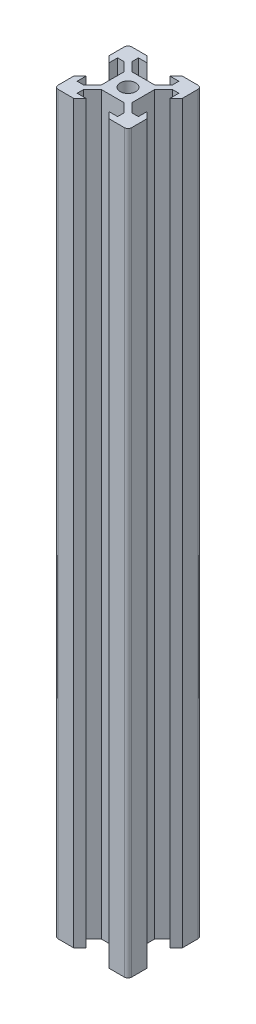
SolidWorks part; units mm, degrees
material "1060 Alloy"
ref_plane "Front Plane" through (0, 0, 0) normal (0, 0, 1) x (1, 0, 0)
ref_plane "Top Plane" through (0, 0, 0) normal (0, 1, 0) x (1, 0, 0)
ref_plane "Right Plane" through (0, 0, 0) normal (1, 0, 0) x (0, 0, -1)
ref_plane "End Plane" through (0, 200, 0) normal (0, 1, 0) x (1, 0, 0)
sketch "MasterLayoutSketch" plane through (0, 0, 0) normal (0, 1, 0) x (1, 0, 0)
  line L0 (-8.325, 3.1) -> (-8.325, 5.5)
  line L1 (-10, -10) -> (10, -10) construction
  line L2 (-10, -10) -> (-10, 10) construction
  line L3 (-10, 10) -> (10, 10) construction
  line L4 (10, -10) -> (10, 10) construction
  line L5 (-10, -10) -> (10, 10) construction
  line L6 (-10, 10) -> (10, -10) construction
  line L7 (-4.775, 10) -> (-3.1, 8.325)
  line L10 (-8.325, 5.5) -> (-6.5607, 5.5)
  line L11 (-10, 4.775) -> (-8.325, 3.1)
  line L12 (-5.5, 8.325) -> (-5.5, 6.5607)
  line L13 (-3.1, 8.325) -> (-5.5, 8.325)
  line L14 (-10, 10) -> (-10, 4.775)
  line L19 (3.1, 8.325) -> (5.5, 8.325)
  line L20 (10, 4.775) -> (8.325, 3.1)
  line L21 (-10, 10) -> (-4.775, 10)
  line L22 (-6.5607, 5.5) -> (-4.1607, 3.1)
  line L23 (-5.5, 6.5607) -> (-3.1, 4.1607)
  line L24 (5.5, 8.325) -> (5.5, 6.5607)
  line L25 (4.775, 10) -> (3.1, 8.325)
  line L26 (8.325, 5.5) -> (6.5607, 5.5)
  line L27 (8.325, 3.1) -> (8.325, 5.5)
  line L28 (10, 10) -> (4.775, 10)
  line L29 (10, 10) -> (10, 4.775)
  line L30 (5.5, 6.5607) -> (3.1, 4.1607)
  line L31 (6.5607, 5.5) -> (4.1607, 3.1)
  line L32 (8.325, -3.1) -> (8.325, -5.5)
  line L33 (4.775, -10) -> (3.1, -8.325)
  line L34 (8.325, -5.5) -> (6.5607, -5.5)
  line L35 (10, -4.775) -> (8.325, -3.1)
  line L36 (5.5, -8.325) -> (5.5, -6.5607)
  line L37 (3.1, -8.325) -> (5.5, -8.325)
  line L38 (10, -10) -> (10, -4.775)
  line L39 (10, -10) -> (4.775, -10)
  line L40 (6.5607, -5.5) -> (4.1607, -3.1)
  line L41 (5.5, -6.5607) -> (3.1, -4.1607)
  line L42 (-3.1, -8.325) -> (-5.5, -8.325)
  line L43 (-10, -4.775) -> (-8.325, -3.1)
  line L44 (-5.5, -8.325) -> (-5.5, -6.5607)
  line L45 (-4.775, -10) -> (-3.1, -8.325)
  line L46 (-8.325, -5.5) -> (-6.5607, -5.5)
  line L47 (-8.325, -3.1) -> (-8.325, -5.5)
  line L48 (-10, -10) -> (-4.775, -10)
  line L49 (-10, -10) -> (-10, -4.775)
  line L50 (-5.5, -6.5607) -> (-3.1, -4.1607)
  line L51 (-6.5607, -5.5) -> (-4.1607, -3.1)
  line L52 (-4.1607, 3.1) -> (-4.1607, -3.1)
  line L53 (-3.1, -4.1607) -> (3.1, -4.1607)
  line L54 (4.1607, -3.1) -> (4.1607, 3.1)
  line L55 (-3.1, 4.1607) -> (3.1, 4.1607)
  circle A0 centre (0, 0) radius 2.1
  point P0 (0, 0)
  point P9 (0, 0)
  dimension "D6" = 4.2
  dimension "D1" = 20
  dimension "D2" = 4
  dimension "D3" = 11
  dimension "D4" = 9.55
  dimension "D5" = 6.2
  dimension "D7" = 1.5
extrude "Main Extrusion" add sketch "MasterLayoutSketch" along normal up to surface (200 mm away) up to plane "End Plane"
cosmetic thread "Cosmetic Thread1" parameters "D1"=11, "D2"=5
cosmetic thread "Cosmetic Thread3" parameters "D1"=11, "D2"=5
fillet "Edge Fillets" radius 1 4 edges at (10, 100, -10) (10, 100, 10) (-10, 100, 10) (-10, 100, -10)
sketch "End Thread Start" plane through (0, 200, 0) normal (0, 1, 0) x (1, 0, 0)
  point P0 (0, 0)
hole_wizard "M5 Tapped Hole1" positions "Sketch3" profile "Sketch4" tap size "M5" standard "ISO"
sketch "Sketch3" plane through (0, 0, 0) normal (0, -1, 0) x (-1, 0, 0)
  point P0 (0, 0)
sketch "Sketch4" plane through (0, 0, 0) normal (1, 0, 0) x (0, 0, -1)
  line L0 (0, 0) -> (0, 13.6618)
  line L1 (0, 13.6618) -> (2.1, 12.4)
  line L2 (2.1, 12.4) -> (2.1, 0)
  line L5 (2.1, 0) -> (0, 0)
  line L10 (0, 13.6618) -> (-2.1, 12.4) construction
  line L11 (0, -6.35) -> (0, 107.95) construction
  dimension "Tap Drill Dia." = 4.2
  dimension "Tap Drill Depth" = 12.4
  dimension "Drill Angle" = 118
